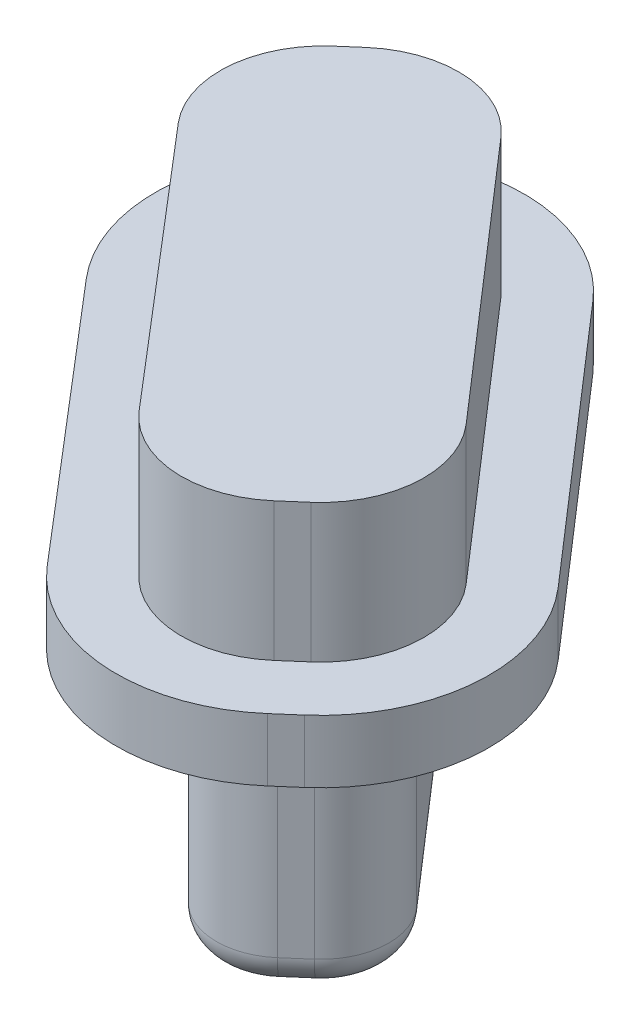
SolidWorks part; units mm, degrees
material "ABS"
ref_plane "X-Y Datum" through (0, 0, 0) normal (0, 0, 1) x (1, 0, 0)
ref_plane "X-Z Datum" through (0, 0, 0) normal (0, 1, 0) x (1, 0, 0)
ref_plane "Y-Z Datum" through (0, 0, 0) normal (1, 0, 0) x (0, 0, -1)
sketch "Sketch1" plane through (0, 0, 0) normal (0, 1, 0) x (1, 0, 0)
  line L0 (-404.3251, -65.8198) -> (-415.9269, -52.2404) construction
  line L1 (-414.5139, -44.3386) -> (-415.3974, -45.1067) construction
  line L2 (-397.13, -66.3539) -> (-396.1311, -65.4856) construction
  line L3 (-395.63, -58.3189) -> (-407.3472, -44.8398) construction
  line L4 (-404.3251, -65.8198) -> (-415.9269, -52.2404)
  line L5 (-414.5139, -44.3386) -> (-415.3974, -45.1067)
  line L6 (-397.13, -66.3539) -> (-396.1311, -65.4856)
  line L7 (-395.63, -58.3189) -> (-407.3472, -44.8398)
  line L8 (-395.5341, -58.2356) -> (-407.2513, -44.7564)
  line L9 (-398.8619, -73.6521) -> (-367.8962, -46.734)
  line L10 (-438.307, -28.2758) -> (-398.8619, -73.6521)
  line L11 (-401.3035, 3.8908) -> (-438.307, -28.2758)
  line L12 (-400.6475, 3.1361) -> (-401.3035, 3.8908)
  line L13 (-406.6852, -2.1124) -> (-400.6475, 3.1361)
  line L14 (-392.2519, -18.716) -> (-406.6852, -2.1124)
  line L15 (-386.2142, -13.4675) -> (-392.2519, -18.716)
  line L16 (-361.8585, -41.4856) -> (-386.2142, -13.4675)
  line L17 (-367.8962, -46.734) -> (-361.8585, -41.4856)
  line L18 (-398.8619, -73.6521) -> (-367.8962, -46.734)
  line L19 (-438.307, -28.2758) -> (-398.8619, -73.6521)
  line L20 (-401.3035, 3.8908) -> (-438.307, -28.2758)
  line L21 (-400.6475, 3.1361) -> (-401.3035, 3.8908)
  line L22 (-406.6852, -2.1124) -> (-400.6475, 3.1361)
  line L23 (-392.2519, -18.716) -> (-406.6852, -2.1124)
  line L24 (-386.2142, -13.4675) -> (-392.2519, -18.716)
  line L25 (-361.8585, -41.4856) -> (-386.2142, -13.4675)
  line L26 (-367.8962, -46.734) -> (-361.8585, -41.4856)
  line L27 (-414.5972, -44.2428) -> (-415.4807, -45.0108)
  line L28 (-404.4216, -65.9023) -> (-416.0235, -52.3229)
  line L29 (-397.0467, -66.4497) -> (-396.0478, -65.5814)
  arc A0 (-415.3974, -45.1067) -> (-415.9269, -52.2404) centre (-412.0646, -48.9406) ccw construction
  arc A1 (-407.3472, -44.8398) -> (-414.5139, -44.3386) centre (-411.1811, -48.1725) ccw construction
  arc A2 (-404.3251, -65.8198) -> (-397.13, -66.3539) centre (-400.4628, -62.52) ccw construction
  arc A3 (-396.1311, -65.4856) -> (-395.63, -58.3189) centre (-399.4639, -61.6517) ccw construction
  arc A4 (-415.3974, -45.1067) -> (-415.9269, -52.2404) centre (-412.0646, -48.9406) ccw
  arc A5 (-407.3472, -44.8398) -> (-414.5139, -44.3386) centre (-411.1811, -48.1725) ccw
  arc A6 (-404.3251, -65.8198) -> (-397.13, -66.3539) centre (-400.4628, -62.52) ccw
  arc A7 (-396.1311, -65.4856) -> (-395.63, -58.3189) centre (-399.4639, -61.6517) ccw
  arc A8 (-407.2513, -44.7564) -> (-414.5972, -44.2428) centre (-411.1811, -48.1725) ccw
  arc A9 (-415.4807, -45.0108) -> (-416.0235, -52.3229) centre (-412.0646, -48.9406) ccw
  arc A10 (-404.4216, -65.9023) -> (-397.0467, -66.4497) centre (-400.4628, -62.52) ccw
  arc A11 (-396.0478, -65.5814) -> (-395.5341, -58.2356) centre (-399.4639, -61.6517) ccw
  dimension "D1" = 0
  dimension "D2" = 0.127
extrude "Boss-Extrude1" add sketch "Sketch1" along normal blind 7 contours L6 A7 L7 A5 L5 A4 L4 A6 | L29 A11 L8 A8 L27 A9 L28 A10 A7 L6 A6 L4 A4 L5 A5 L7
sketch "Sketch3" plane through (0, 0, 0) normal (0, -1, 0) x (1, 0, 0)
  line L0 (-406.9321, 68.0472) -> (-418.534, 54.4678)
  line L1 (-417.6471, 42.5188) -> (-416.7635, 41.7507)
  line L2 (-404.7593, 42.5901) -> (-393.0421, 56.0693)
  line L3 (-393.8815, 68.0735) -> (-394.8804, 68.9418)
  line L4 (-396.0478, 65.5814) -> (-397.0467, 66.4497)
  line L6 (-396.0478, 65.5814) -> (-397.0467, 66.4497)
  line L16 (-404.4216, 65.9023) -> (-416.0235, 52.3229)
  line L17 (-404.4216, 65.9023) -> (-416.0235, 52.3229)
  line L18 (-415.4807, 45.0108) -> (-414.5972, 44.2428)
  line L19 (-415.4807, 45.0108) -> (-414.5972, 44.2428)
  line L20 (-407.2513, 44.7564) -> (-395.5341, 58.2356)
  line L22 (-407.2513, 44.7564) -> (-395.5341, 58.2356)
  arc A0 (-418.534, 54.4678) -> (-417.6471, 42.5188) centre (-412.0646, 48.9406) ccw
  arc A1 (-416.7635, 41.7507) -> (-404.7593, 42.5901) centre (-411.1811, 48.1725) ccw
  arc A2 (-393.0421, 56.0693) -> (-393.8815, 68.0735) centre (-399.4639, 61.6517) ccw
  arc A3 (-394.8804, 68.9418) -> (-406.9321, 68.0472) centre (-400.4628, 62.52) ccw
  arc A12 (-397.0467, 66.4497) -> (-404.4216, 65.9023) centre (-400.4628, 62.52) ccw
  arc A13 (-397.0467, 66.4497) -> (-404.4216, 65.9023) centre (-400.4628, 62.52) ccw
  arc A14 (-416.0235, 52.3229) -> (-415.4807, 45.0108) centre (-412.0646, 48.9406) ccw
  arc A15 (-416.0235, 52.3229) -> (-415.4807, 45.0108) centre (-412.0646, 48.9406) ccw
  arc A16 (-414.5972, 44.2428) -> (-407.2513, 44.7564) centre (-411.1811, 48.1725) ccw
  arc A17 (-414.5972, 44.2428) -> (-407.2513, 44.7564) centre (-411.1811, 48.1725) ccw
  arc A18 (-395.5341, 58.2356) -> (-396.0478, 65.5814) centre (-399.4639, 61.6517) ccw
  arc A19 (-395.5341, 58.2356) -> (-396.0478, 65.5814) centre (-399.4639, 61.6517) ccw
  line M17 (-396.0478, 65.5814) -> (-397.0467, 66.4497)
  arc M18 (-397.0467, 66.4497) -> (-404.4216, 65.9023) centre (-400.4628, 62.52) ccw
  line M19 (-404.4216, 65.9023) -> (-416.0235, 52.3229)
  arc M20 (-416.0235, 52.3229) -> (-415.4807, 45.0108) centre (-412.0646, 48.9406) ccw
  line M21 (-415.4807, 45.0108) -> (-414.5972, 44.2428)
  arc M22 (-414.5972, 44.2428) -> (-407.2513, 44.7564) centre (-411.1811, 48.1725) ccw
  line M23 (-407.2513, 44.7564) -> (-395.5341, 58.2356)
  arc M24 (-395.5341, 58.2356) -> (-396.0478, 65.5814) centre (-399.4639, 61.6517) ccw
  dimension "D1" = 0
extrude "Boss-Extrude3" add sketch "Sketch3" along normal blind 3.175 contours M24 M17 M18 M19 M20 M21 M22 M23 | L3 A3 L0 A0 L1 A1 L2 A2 M17 M24 M23 M22 M21 M20 M19 M18
sketch "Sketch4" plane through (0, -3.175, 0) normal (0, -1, 0) x (1, 0, 0)
  line L0 (-403.0698, 64.7474) -> (-414.6717, 51.168)
  line L1 (-414.3143, 46.3527) -> (-413.4307, 45.5846)
  line L2 (-408.5932, 45.9229) -> (-396.876, 59.402)
  line L3 (-397.2143, 64.2396) -> (-398.2131, 65.1079)
  line L4 (-393.8815, 68.0735) -> (-394.8804, 68.9418)
  line L5 (-406.9321, 68.0472) -> (-418.534, 54.4678)
  line L6 (-417.6471, 42.5188) -> (-416.7635, 41.7507)
  line L7 (-404.7593, 42.5901) -> (-393.0421, 56.0693)
  line L8 (-393.8815, 68.0735) -> (-394.8804, 68.9418)
  line L10 (-417.6471, 42.5188) -> (-416.7635, 41.7507)
  line L11 (-404.7593, 42.5901) -> (-393.0421, 56.0693)
  line L16 (-406.9321, 68.0472) -> (-418.534, 54.4678) construction
  line L18 (-406.9321, 68.0472) -> (-418.534, 54.4678)
  arc A0 (-414.6717, 51.168) -> (-414.3143, 46.3527) centre (-412.0646, 48.9406) ccw
  arc A1 (-413.4307, 45.5846) -> (-408.5932, 45.9229) centre (-411.1811, 48.1725) ccw
  arc A2 (-396.876, 59.402) -> (-397.2143, 64.2396) centre (-399.4639, 61.6517) ccw
  arc A3 (-398.2131, 65.1079) -> (-403.0698, 64.7474) centre (-400.4628, 62.52) ccw
  arc A4 (-394.8804, 68.9418) -> (-406.9321, 68.0472) centre (-400.4628, 62.52) ccw
  arc A5 (-418.534, 54.4678) -> (-417.6471, 42.5188) centre (-412.0646, 48.9406) ccw
  arc A6 (-416.7635, 41.7507) -> (-404.7593, 42.5901) centre (-411.1811, 48.1725) ccw
  arc A7 (-393.0421, 56.0693) -> (-393.8815, 68.0735) centre (-399.4639, 61.6517) ccw
  arc A8 (-394.8804, 68.9418) -> (-406.9321, 68.0472) centre (-400.4628, 62.52) ccw
  arc A9 (-418.534, 54.4678) -> (-417.6471, 42.5188) centre (-412.0646, 48.9406) ccw
  arc A10 (-416.7635, 41.7507) -> (-404.7593, 42.5901) centre (-411.1811, 48.1725) ccw
  arc A11 (-393.0421, 56.0693) -> (-393.8815, 68.0735) centre (-399.4639, 61.6517) ccw
  dimension "D1" = 0
  dimension "D2" = 5.08
extrude "Boss-Extrude4" add sketch "Sketch4" along normal blind 12.7 contours L3 A3 L0 A0 L1 A1 L2 A2
fillet "Fillet2" radius 1.5875 8 edges at (-410.9419, -15.875, 44.7519) (-413.8725, -15.875, 45.9687) (-415.4842, -15.875, 48.6868) (-408.8708, -15.875, 57.9577) (-400.7166, -15.875, 65.9395) (-397.7137, -15.875, 64.6737) (-396.0433, -15.875, 61.8909) (-402.7346, -15.875, 52.6625)
